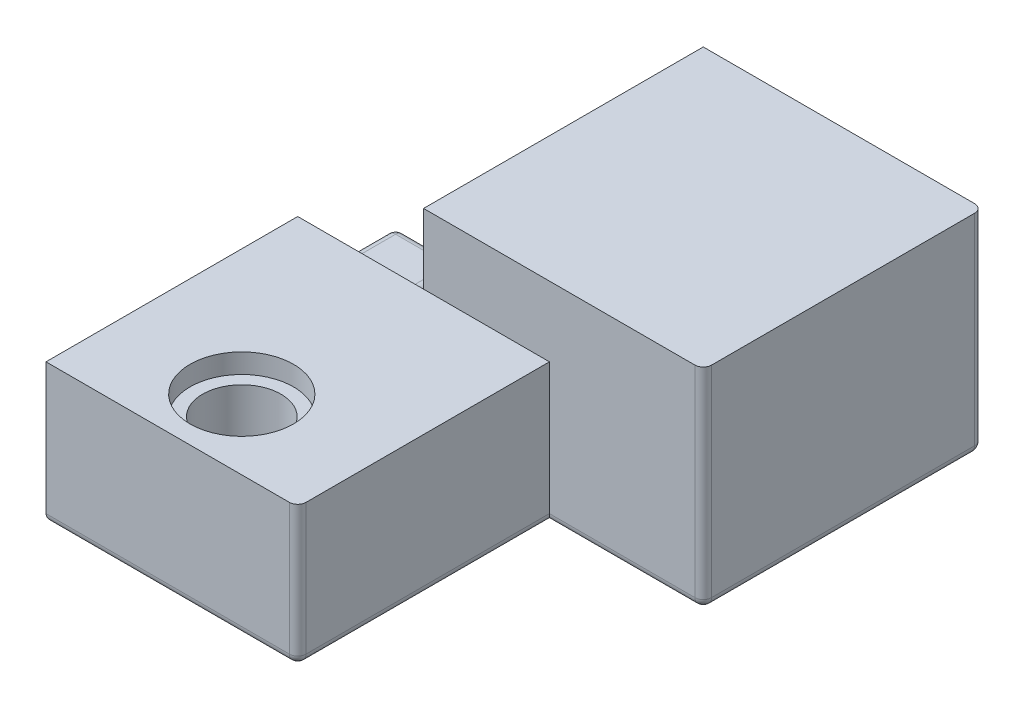
SolidWorks part; units mm, degrees
ref_plane "Front Plane" through (0, 0, 0) normal (0, 0, 1) x (1, 0, 0)
ref_plane "Top Plane" through (0, 0, 0) normal (0, 1, 0) x (1, 0, 0)
ref_plane "Right Plane" through (0, 0, 0) normal (1, 0, 0) x (0, 0, -1)
sketch "Sketch1" plane through (0, 0, 0) normal (0, 1, 0) x (1, 0, 0)
  line L0 (0, 0) -> (-133401.8874, 0) construction
  line L1 (0, 0) -> (0, -133401.8874) construction
  line L3 (-50, 50) -> (50, 50)
  line L4 (-50, 50) -> (-50, -50)
  line L5 (-50, -50) -> (50, -50)
  line L6 (50, 50) -> (50, -50)
  line L7 (-50, 50) -> (50, -50) construction
  line L8 (-50, -50) -> (50, 50) construction
  point P5 (0, 0)
  dimension "D1" = 100
extrude "Boss-Extrude1" add sketch "Sketch1" along normal blind 50
sketch "Sketch8" plane through (0, 50, 0) normal (0, 1, 0) x (1, 0, 0)
  line L0 (0, 0) -> (-50000, 0) construction
  line L1 (0, 0) -> (0, -50000) construction
  line L2 (-50, -50) -> (50, -50) construction
  line L3 (-95, -140) -> (-5, -140)
  line L4 (-95, -140) -> (-95, -50)
  line L5 (-95, -50) -> (-5, -50)
  line L6 (-5, -140) -> (-5, -50)
  line L7 (-95, -140) -> (-5, -50) construction
  line L8 (-95, -50) -> (-5, -140) construction
  line L9 (-50, -95) -> (-50, -50095) construction
  line L10 (50, -50) -> (50, 50) construction
  point P5 (-50, -95)
  dimension "D1" = 90
  dimension "D2" = 90
  dimension "D3" = 100
extrude "Boss-Extrude4" add sketch "Sketch8" against normal up to surface (50 mm away) up to face at (0, 0, 0)
sketch "Sketch9" plane through (0, 50, 0) normal (0, 1, 0) x (1, 0, 0)
  line L0 (50, -50) -> (50, 50) construction
  line L1 (0, 0) -> (-50000, 0) construction
  line L4 (-50, -50) -> (-95, -50) construction
  circle A0 centre (-50, -115) radius 18.5
  dimension "D1" = 37
  dimension "D2" = 65
  dimension "D3" = 100
extrude "Cut-Extrude1" cut sketch "Sketch9" against normal blind 7
sketch "Sketch10" plane through (0, 50, 0) normal (0, 1, 0) x (1, 0, 0)
  line L0 (0, 0) -> (-50000, 0) construction
  line L1 (0, 0) -> (0, -50000) construction
  circle A0 centre (-50, -115) radius 14
  dimension "D1" = 28
extrude "Cut-Extrude2" cut sketch "Sketch10" against normal blind 25
sketch "Sketch11" plane through (0, 0, 50) normal (0, 0, -1) x (-1, 0, 0)
  line L0 (0, 0) -> (0, -50000) construction
  line L1 (72.5, 50) -> (72.5, -49950) construction
  line L2 (50, 50) -> (95, 50) construction
  line L3 (95, 25) -> (-49905, 25) construction
  line L4 (95, 0) -> (95, 50) construction
  line L6 (60, 40) -> (85, 40)
  line L7 (60, 40) -> (60, 10)
  line L8 (60, 10) -> (85, 10)
  line L9 (85, 40) -> (85, 10)
  line L10 (60, 40) -> (85, 10) construction
  line L11 (60, 10) -> (85, 40) construction
  point P7 (72.5, 50)
  point P12 (95, 25)
  point P13 (72.5, 25)
  dimension "D1" = 25
  dimension "D2" = 30
extrude "Boss-Extrude5" add sketch "Sketch11" along normal blind 25
sketch "Sketch12" plane through (0, 50, 0) normal (0, 1, 0) x (1, 0, 0)
  line L0 (0, 0) -> (-50000, 0) construction
  line L1 (0, 0) -> (0, -50000) construction
  line L3 (-50, 50) -> (50, 50)
  line L4 (-50, 50) -> (-50, -50)
  line L5 (-50, -50) -> (50, -50)
  line L6 (50, 50) -> (50, -50)
  line L7 (-50, 50) -> (50, -50) construction
  line L8 (-50, -50) -> (50, 50) construction
  point P5 (0, 0)
extrude "Boss-Extrude6" add sketch "Sketch12" along normal blind 25
sketch "Sketch13" plane through (0, 0, -50) normal (0, 0, -1) x (-1, 0, 0)
  line L0 (0, 0) -> (0, -50000) construction
  line L1 (-50, 0) -> (50, 0) construction
  line L2 (-50, 37.5) -> (49950, 37.5) construction
  line L3 (-50, 75) -> (-50, 0) construction
  line L4 (50, 75) -> (50, 0) construction
  line L5 (30, 12.5) -> (50, 12.5)
  line L6 (30, 12.5) -> (30, 62.5)
  line L7 (30, 62.5) -> (50, 62.5)
  line L8 (50, 12.5) -> (50, 62.5)
  line L9 (30, 12.5) -> (50, 62.5) construction
  line L10 (30, 62.5) -> (50, 12.5) construction
  point P4 (0, 0)
  point P9 (-50, 37.5)
  point P10 (40, 37.5)
  dimension "D1" = 20
  dimension "D2" = 50
extrude "Cut-Extrude3" cut sketch "Sketch13" against normal blind 50
sketch "Sketch14" plane through (0, 10, 0) normal (0, -1, 0) x (1, 0, 0)
  line L0 (0, 0) -> (-50000, 0) construction
  line L1 (0, 0) -> (0, -50000) construction
  line L2 (-72.5, 50) -> (-72.5, -49950) construction
  line L3 (-95, 50) -> (-50, 50) construction
  line L4 (-60, 37.5) -> (-50060, 37.5) construction
  line L5 (-60, 25) -> (-60, 50) construction
  line L6 (-85, 25) -> (-85, 50) construction
  circle A0 centre (-72.5, 37.5) radius 2
  point P9 (-72.5, 50)
  point P14 (-60, 37.5)
  dimension "D1" = 4
extrude "Cut-Extrude4" cut sketch "Sketch14" against normal blind 15
sketch "Sketch15" plane through (0, 0, 0) normal (0, -1, 0) x (1, 0, 0)
  line L0 (0, 0) -> (-50000, 0) construction
  line L1 (0, 0) -> (0, -50000) construction
  line L2 (-40, -50) -> (-40, -50050) construction
  line L4 (-50, -50) -> (-50, 50) construction
  line L5 (-50, -25) -> (49950, -25) construction
  line L6 (50, -50) -> (-50, -50) construction
  circle A0 centre (-40, -37.5) radius 2.5
  circle A1 centre (-40, -12.5) radius 2.5
  dimension "D3" = 5
  dimension "D4" = 12.5
  dimension "D1" = 10
  dimension "D2" = 25
extrude "Cut-Extrude5" cut sketch "Sketch15" against normal blind 15
sketch "Sketch16" plane through (0, 0, 0) normal (0, -1, 0) x (1, 0, 0)
  line L0 (0, 0) -> (0, -50000) construction
  line L1 (0, 0) -> (-50000, 0) construction
  line L2 (-40, -37.5) -> (-40, -50037.5) construction
  line L3 (-40, -25) -> (-50040, -25) construction
  line L5 (50, -50) -> (-50, -50) construction
  circle A0 centre (-40, -37.5) radius 3.75
  circle A1 centre (-40, -12.5) radius 3.75
  dimension "D2" = 7.5
  dimension "D1" = 25
extrude "Cut-Extrude6" cut sketch "Sketch16" against normal blind 4
fillet "Fillet1" radius 3 18 edges at (-72.5, 10, 25) (-85, 25, 25) (-72.5, 40, 25) (-60, 25, 25) (-60, 40, 37.5) (-60, 10, 37.5) (-85, 40, 37.5) (-85, 10, 37.5) (-5, 25, 140) (-50, 0, 140) (-5, 0, 95) (22.5, 0, 50) (50, 37.5, 50) (50, 0, 0) (0, 0, -50) (50, 37.5, -50) (-95, 0, 95) (-72.5, 0, 50)
